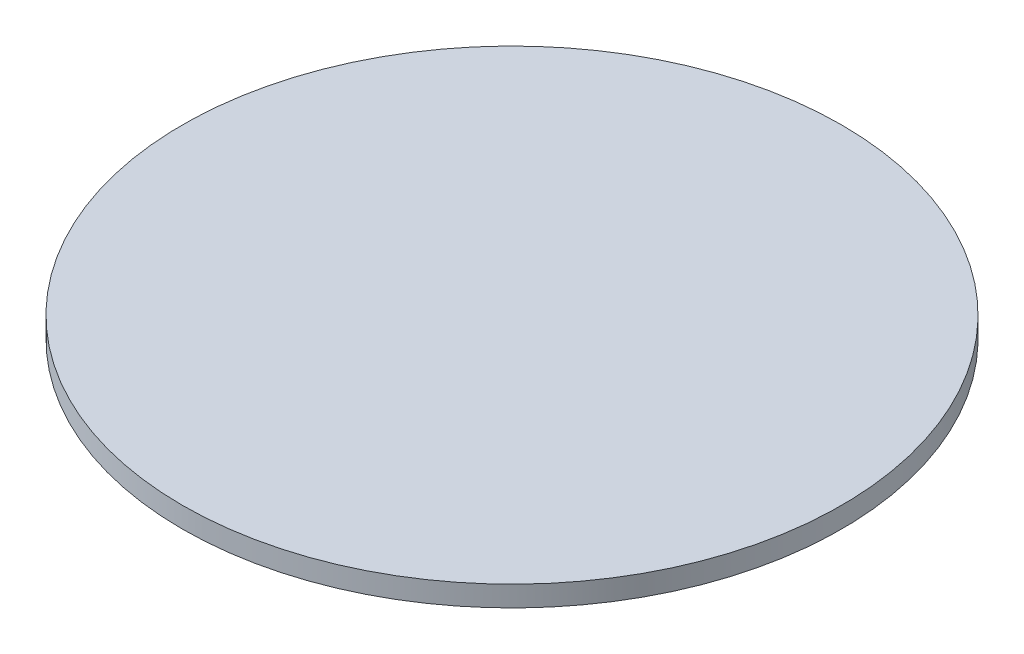
SolidWorks part; units mm, degrees
material "ABS PC"
ref_plane "Front Plane" through (0, 0, 0) normal (0, 0, 1) x (1, 0, 0)
ref_plane "Top Plane" through (0, 0, 0) normal (0, 1, 0) x (1, 0, 0)
ref_plane "Right Plane" through (0, 0, 0) normal (1, 0, 0) x (0, 0, -1)
sketch "Sketch1" plane through (0, 0, 0) normal (0, 1, 0) x (1, 0, 0)
  circle A1 centre (0, 0) radius 4.05
  circle A2 centre (0, 0) radius 16
  circle A3 centre (0, 8) radius 1
  circle A4 centre (5.6569, 5.6569) radius 1
  circle A5 centre (8, 0) radius 1
  circle A6 centre (5.6569, -5.6569) radius 1
  circle A7 centre (0, -8) radius 1
  circle A8 centre (-5.6569, -5.6569) radius 1
  circle A9 centre (-8, 0) radius 1
  circle A10 centre (-5.6569, 5.6569) radius 1
  dimension "D1" = 8
  dimension "D2" = 8
  dimension "D3" = 8.1
  dimension "D4" = 2
extrude "Boss-Extrude1" add sketch "Sketch1" along normal blind 1 contours A3 | A2 A10 A9 A8 A7 A6 A5 A4 A3 A1 | A1 | A10 | A8 | A7 | A6 | A5 | A4
